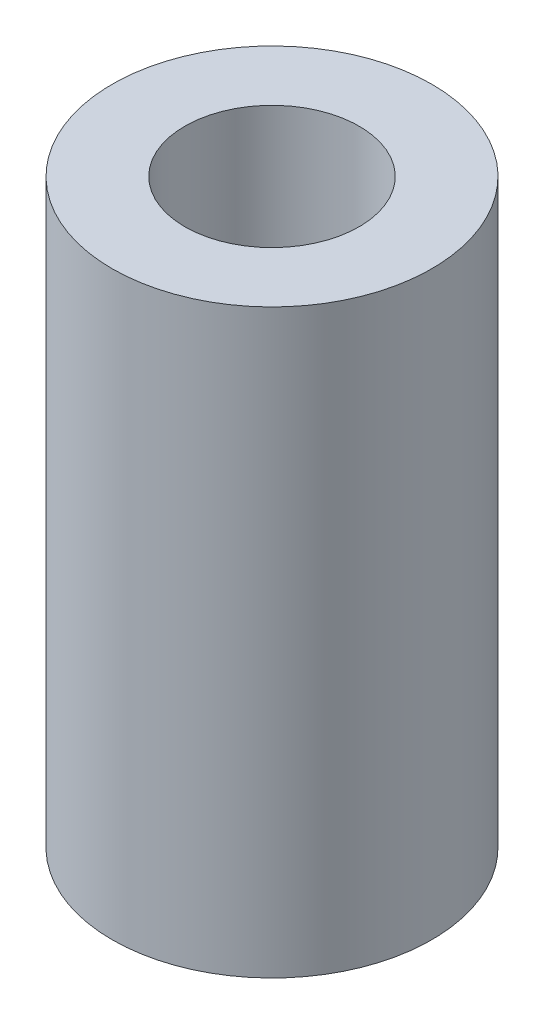
SolidWorks part; units mm, degrees
ref_plane "Front Plane" through (0, 0, 0) normal (0, 0, 1) x (1, 0, 0)
ref_plane "Top Plane" through (0, 0, 0) normal (0, 1, 0) x (1, 0, 0)
ref_plane "Right Plane" through (0, 0, 0) normal (1, 0, 0) x (0, 0, -1)
sketch "Sketch1" plane through (0, 0, 0) normal (0, 1, 0) x (1, 0, 0)
  circle A0 centre (0, 0) radius 1.8
  circle A1 centre (0, 0) radius 3.3
  dimension "D1" = 3.6
  dimension "D2" = 1.5
extrude "Boss-Extrude1" add sketch "Sketch1" along normal blind 12
